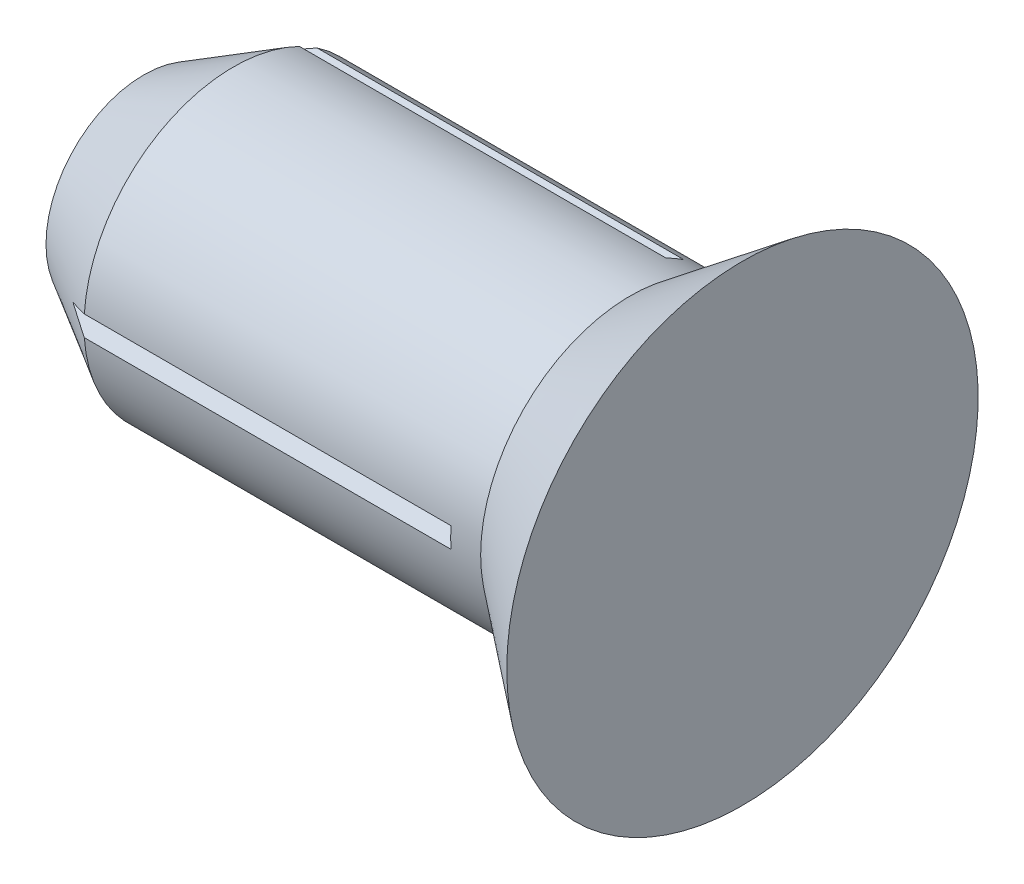
SolidWorks part; units mm, degrees
revolve "Base-Revolve" add sketch "Sketch1" angle 360 about L0
sketch "Sketch1" plane through (0, 0, 0) normal (0, 0, 1) x (1, 0, 0)
  line L0 (-40, 0) -> (40, 0) construction
  line L1 (-32.5065, 0) -> (-32.5065, 6.5359)
  line L2 (-26.5065, 10) -> (0, 10)
  line L3 (0, 10) -> (7.4935, 15.75)
  line L4 (7.4935, 15.75) -> (7.4935, 0)
  line L5 (0, -10) -> (7.4935, -15.75) construction
  line L6 (7.4935, 0) -> (-32.5065, 0)
  line L7 (-32.5065, 6.5359) -> (-26.5065, 10)
  dimension "D1" = 30
  dimension "HeadDia" = 31.5
  dimension "D2" = 75
  dimension "Diameter" = 20
  dimension "Length" = 40
  dimension "ChamferLength" = 6
ref_plane "Plane1" through (0, 0, 0) normal (0, 0, 1) x (1, 0, 0)
ref_plane "Plane2" through (0, 0, 0) normal (0, 1, 0) x (1, 0, 0)
ref_plane "Plane3" through (0, 0, 0) normal (1, 0, 0) x (0, 0, -1)
sketch "Sketch2" plane through (-32.5065, 0, 0) normal (-1, 0, 0) x (0, 0, 1)
  line L0 (0, 0) -> (12, 0) construction
  line L1 (9, 0) -> (10, 0.7002)
  line L2 (9, 0) -> (10, -0.7002)
  line L3 (10, -0.7002) -> (10, 0.7002)
  circle A0 centre (0, 0) radius 9 construction
  circle A1 centre (0, 0) radius 10 construction
  dimension "D1" = 18
  dimension "D2" = 70
  dimension "D3" = 35
extrude "Cut-Extrude1" cut sketch "Sketch2" against normal blind 30.5065
pattern_circular "CirPattern1" count 3 over 360 about axis through (0, 0, 0) along (1, 0, 0) of "Cut-Extrude1"
equation "\"D1@Sketch2\" = \"Diameter@Sketch1\" * .9"
equation "\"D3@Sketch2\" = \"D2@Sketch2\" / 2"
equation "\"D1@Cut-Extrude1\" = \"Length@Sketch1\" - (((\"HeadDia@Sketch1\" - \"Diameter@Sketch1\") / 2.0) / tan((37.5 / 180) * 3.14159265)) - \"ChamferLength@Sketch1\" / 3"
